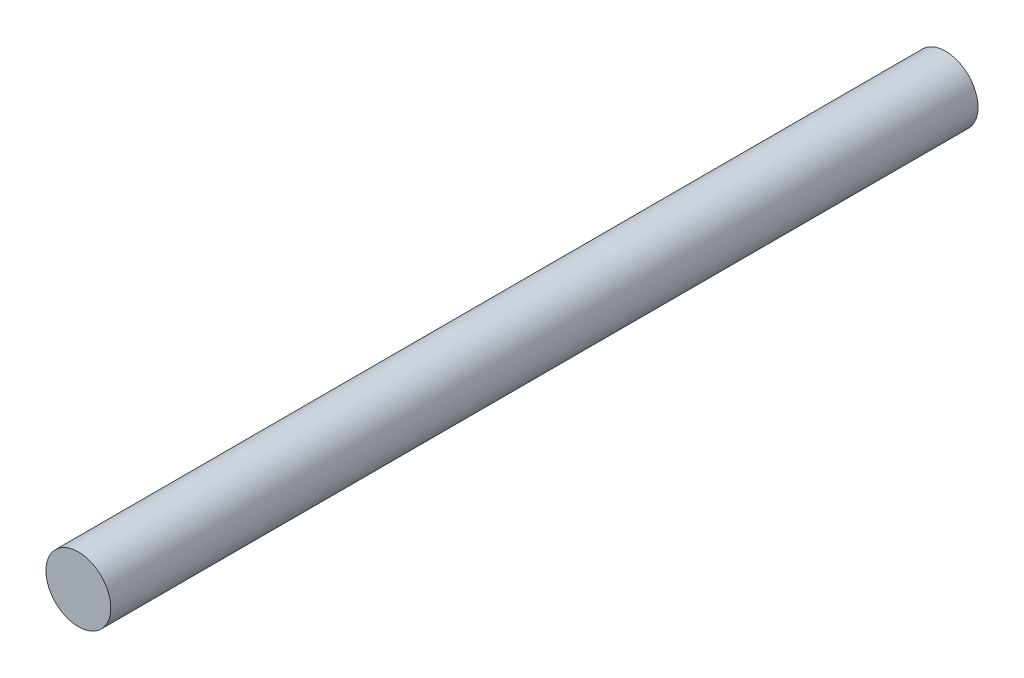
SolidWorks part; units mm, degrees
ref_plane "Front Plane" through (0, 0, 0) normal (0, 0, 1) x (1, 0, 0)
ref_plane "Top Plane" through (0, 0, 0) normal (0, 1, 0) x (1, 0, 0)
ref_plane "Right Plane" through (0, 0, 0) normal (1, 0, 0) x (0, 0, -1)
sketch "Sketch1" plane through (0, 0, 0) normal (0, 0, 1) x (1, 0, 0)
  circle A0 centre (0, 0) radius 4
  dimension "D1" = 8
extrude "Boss-Extrude1" add sketch "Sketch1" along normal blind 107
